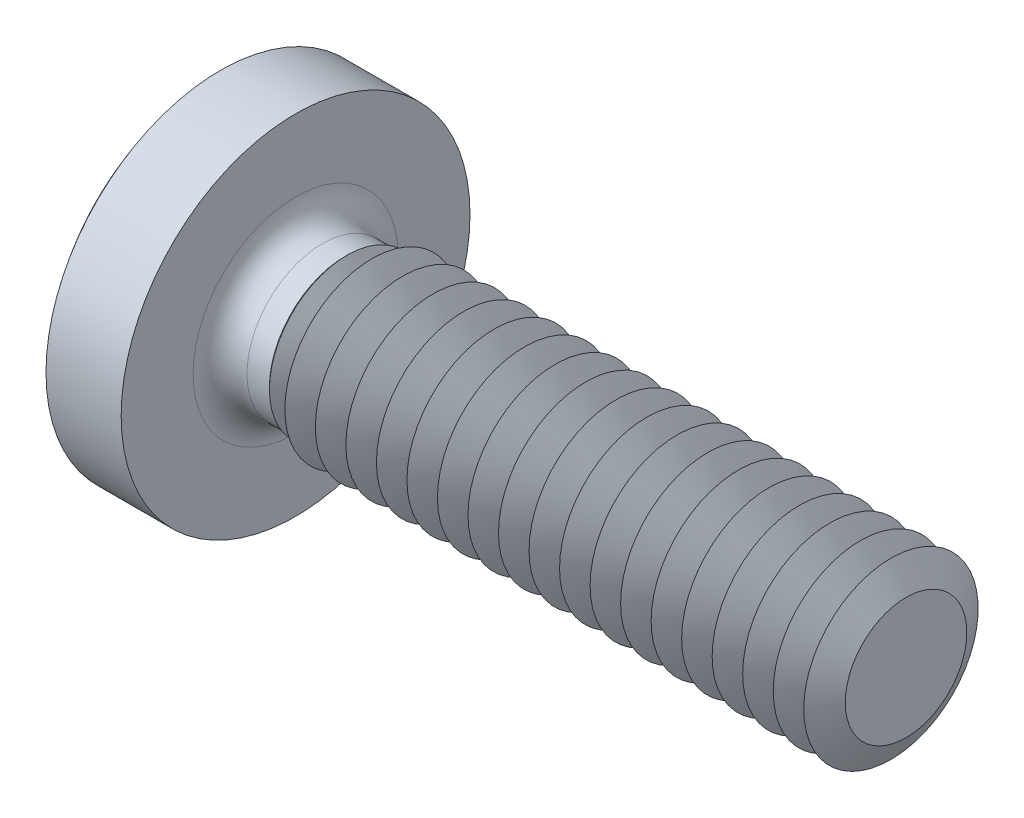
SolidWorks part; units mm, degrees
revolve "基体-旋转" add sketch "草图2" angle 360 about L0
sketch "草图2" plane through (0, 0, 0) normal (0, 0, 1) x (1, 0, 0)
  line L0 (-1.3318, 0) -> (6.5885, 0) construction
  line L1 (0, 0) -> (17.1, 0)
  line L2 (17.1, 0) -> (17.1, 2)
  line L3 (17.1, 2) -> (4.5, 2)
  line L4 (4.5, 2) -> (4.232, 1.732)
  line L5 (4.232, 1.732) -> (3.718, 1.732)
  line L6 (3.1, 2.35) -> (3.1, 4)
  line L7 (3.1, 4) -> (1.3765, 4)
  arc A0 (3.1, 2.35) -> (3.718, 1.732) centre (3.718, 2.35) ccw
  arc A1 (0, 0) -> (1.3765, 4) centre (6.5, 0) cw
  dimension "D3" = 6.5
  dimension "dk" = 8
  dimension "d" = 4
  dimension "l" = 14
  dimension "a" = 1.4
  dimension "D1" = 45
  dimension "D2" = 3.464
  dimension "da" = 4.7
  dimension "k" = 3.1
cosmetic thread "装饰螺纹线1" parameters "D1"=12.6, "D2"=3.464
ref_plane "前视" through (0, 0, 0) normal (0, 0, 1) x (1, 0, 0)
ref_plane "上视" through (0, 0, 0) normal (0, 1, 0) x (1, 0, 0)
ref_plane "右视" through (0, 0, 0) normal (1, 0, 0) x (0, 0, -1)
sketch "尺寸草图" plane through (0, 0, 0) normal (0, 0, 1) x (1, 0, 0)
  line L0 (0, 0) -> (14, 0)
  line L1 (0, 0) -> (0, 8)
  line L2 (14, 0) -> (14, 4.7)
  point P5 (0, 4)
  point P6 (13.3, 0)
  point P7 (1.4, 0)
  point P8 (3.1, 0)
  point P9 (7.5, 0)
  point P10 (4.4, 0)
  point P11 (11.6, 0)
  dimension "dk" = 8
  dimension "d" = 4
  dimension "l" = 14
  dimension "a" = 1.4
  dimension "da" = 4.7
  dimension "k" = 3.1
  dimension "P" = 0.7
  dimension "rf" = 6.5
  dimension "m" = 4.4
  dimension "h" = 2.4
sketch "草图3" plane through (0, 0, 0) normal (0, 0, 1) x (1, 0, 0)
  line L0 (16.7538, 2) -> (17.4538, 2)
  line L1 (17.4538, 2) -> (17.1, 1.3938)
  line L2 (17.1, 1.3938) -> (16.7538, 2)
  line L3 (17.1, 2) -> (4.5, 2) construction
  line L4 (17.1, -2) -> (17.1, 2) construction
  line L5 (-0.2428, 0) -> (7.1644, 0) construction
  line L6 (-1.3318, 0) -> (6.5885, 0) construction
  dimension "P" = 0.7
  dimension "D1" = 0.6062
  dimension "D2" = 60
revolve "切除-旋转1" cut sketch "草图3" angle 360 about L5
sketch "草图5" plane through (0, 0, 0) normal (1, 0, 0) x (0, 0, -1)
  line L1 (0.35, 2.2) -> (-0.35, 2.2)
  line L2 (0.35, 2.2) -> (0.35, -2.2)
  line L3 (0.35, -2.2) -> (-0.35, -2.2)
  line L4 (-0.35, 2.2) -> (-0.35, -2.2)
  point P4 (0.35, 0)
  point P5 (0, 2.2)
  dimension "m" = 4.4
  dimension "D1" = 0.7
ref_plane "基准面1" through (2.4, 0, 0) normal (1, 0, 0) x (0, 0, -1)
pattern_linear "阵列(线性)1" count 19 spacing 0.7 along (-1, 0, 0) of "切除-旋转1"
sketch "草图6" plane through (2.4, 0, 0) normal (1, 0, 0) x (0, 0, -1)
  point P0 (0, 0)
loft "切除-放样1" cut profiles "草图6", "草图5"
ref_plane "基准面2" through (0, 0, 0) normal (0, -0.7071, 0.7071) x (1, 0, 0)
mirror "镜向1" about plane through (0, 0, 0) normal (0, -0.7071, 0.7071) of "切除-放样1"
equation "\"l@草图2\" = \"l@尺寸草图\""
equation "\"dk@草图2\" = \"dk@尺寸草图\""
equation "\"k@草图2\" = \"k@尺寸草图\""
equation "\"D2@草图2\" = \"d@尺寸草图\"*0.866"
equation "\"a@草图2\" = \"a@尺寸草图\""
equation "\"D3@草图2\" = \"rf@尺寸草图\""
equation "\"d@草图2\" = \"d@尺寸草图\""
equation "\"da@草图2\" = \"da@尺寸草图\""
equation "\"D2@装饰螺纹线1\" = \"d@尺寸草图\"*0.866"
equation "\"D1@装饰螺纹线1\" = \"l@尺寸草图\"-\"a@尺寸草图\""
equation "\"P@草图3\" = \"P@尺寸草图\""
equation "\"D1@草图3\" = \"P@尺寸草图\"*0.866"
equation "\"h@基准面1\" = \"h@尺寸草图\""
equation "\"D1@草图5\" = \"P@尺寸草图\""
equation "\"m@草图5\" = \"m@尺寸草图\""
equation "\"D3@阵列(线性)1\" = \"P@尺寸草图\""
equation "\"D1@阵列(线性)1\" = (\"l@尺寸草图\"-\"a@尺寸草图\")/\"P@尺寸草图\"+1"
